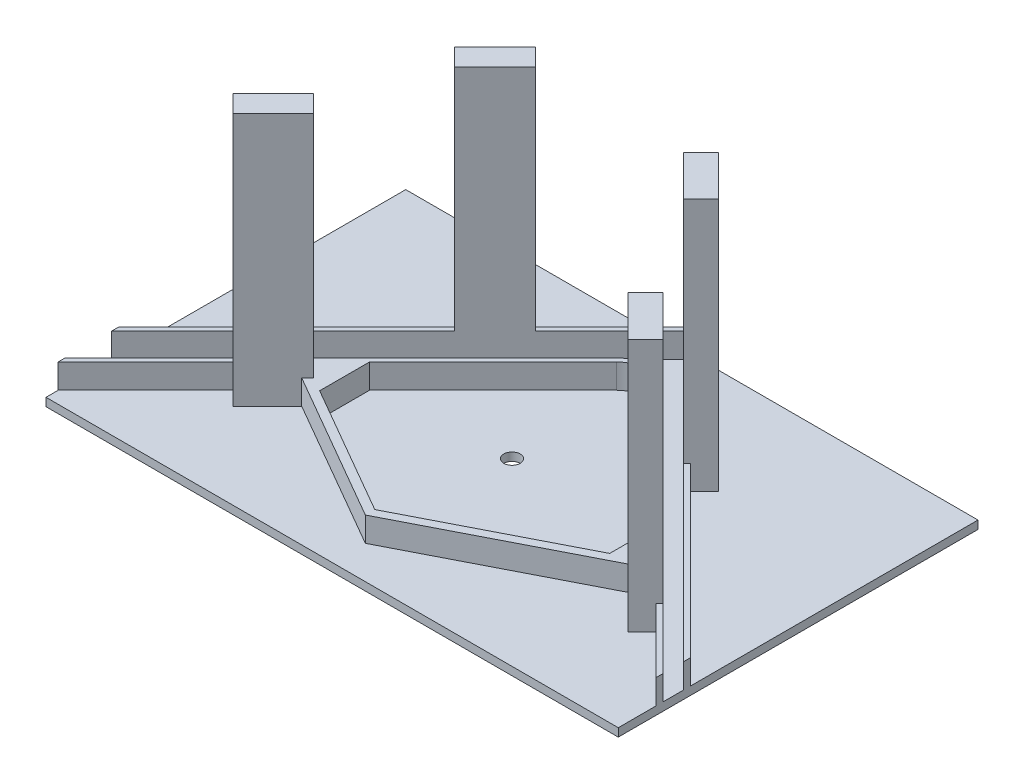
SolidWorks part; units mm, degrees
ref_plane "Alzado" through (0, 0, 0) normal (0, 0, 1) x (1, 0, 0)
ref_plane "Planta" through (0, 0, 0) normal (0, 1, 0) x (1, 0, 0)
ref_plane "Vista lateral" through (0, 0, 0) normal (1, 0, 0) x (0, 0, -1)
sketch "Croquis1" plane through (0, 0, 0) normal (0, 1, 0) x (1, 0, 0)
  line L0 (-225, -110) -> (-225, -210) construction
  line L1 (225, -110) -> (-225, -110) construction
  line L2 (225, -110) -> (225, 110) construction
  line L3 (225, 110) -> (-225, 110) construction
  line L4 (-225, -110) -> (-225, 110) construction
  line L5 (225, -110) -> (-225, 110) construction
  line L6 (225, 110) -> (-225, -110) construction
  line L7 (-225, -210) -> (225, -210) construction
  line L8 (225, -210) -> (225, -110) construction
  line L9 (-5, 0) -> (-5, -110) construction
  line L10 (5, 0) -> (5, -110) construction
  arc A0 (5, 0) -> (-5, 0) centre (0, 0) ccw construction
  point P0 (0, 0)
  dimension "D4" = 10
  dimension "D1" = 450
  dimension "D2" = 220
  dimension "D3" = 100
sketch "Croquis2" plane through (0, 0, 0) normal (0, 1, 0) x (1, 0, 0)
  line L0 (0, 133.4706) -> (0, 87.0581) construction
  line L1 (225, 110) -> (-225, -110) construction
  line L4 (-175, -110) -> (-175, 110)
  line L5 (225, -110) -> (-225, -110) construction
  line L6 (-175, 110) -> (175, 110)
  line L7 (-175, -110) -> (175, -110)
  line L8 (175, -110) -> (175, 110)
  circle A0 centre (0, 0) radius 5
  point P14 (0, -110)
  point P15 (0, 110)
  dimension "D1" = 10
  dimension "D2" = 110
  dimension "D3" = 175
extrude "Saliente-Extruir1" add sketch "Croquis2" along normal blind 20
sketch "Croquis3" plane through (0, 20, 0) normal (0, 1, 0) x (1, 0, 0)
  line L7 (-7.5056, 0) -> (-3.7528, -6.5)
  line L8 (-3.7528, -6.5) -> (3.7528, -6.5)
  line L9 (3.7528, -6.5) -> (7.5056, 0)
  line L10 (7.5056, 0) -> (3.7528, 6.5)
  line L11 (3.7528, 6.5) -> (-3.7528, 6.5)
  line L12 (-3.7528, 6.5) -> (-7.5056, 0)
  circle A0 centre (0, 0) radius 6.5 construction
  dimension "D1" = 13
extrude "Cortar-Extruir1" cut sketch "Croquis3" against normal blind 7
sketch "Croquis8" plane through (0, 20, 0) normal (0, 1, 0) x (1, 0, 0)
  line L0 (0, 132.6182) -> (0, 35.5144) construction
  line L2 (225, 110) -> (-225, 110) construction
  line L3 (21.9203, 70.3518) -> (175, -82.7279)
  line L4 (0, 105) -> (175, -70)
  line L5 (175, -110) -> (175, 110) construction
  line L8 (175, -70) -> (175, -82.7279)
  line L10 (0, 105) -> (-175, -70)
  line L11 (-175, 110) -> (-175, -110) construction
  line L12 (-175, -98.2843) -> (-6.364, 70.3518)
  line L13 (-175, -98.2843) -> (-175, -70)
  arc A0 (-6.364, 70.3518) -> (21.9203, 70.3518) centre (7.7782, 56.2096) cw
  dimension "D5" = 20
  dimension "D1" = 45
  dimension "D2" = 9
  dimension "D3" = 5
  dimension "D4" = 20
extrude "Cortar-Extruir3" cut sketch "Croquis8" against normal blind 15
sketch "Croquis9" plane through (0, 20, 0) normal (0, 1, 0) x (1, 0, 0)
  line L5 (-98.9949, -22.2792) -> (-88.3883, -32.8858)
  line L6 (-88.3883, -32.8858) -> (-113.1371, -57.6346)
  line L7 (-113.1371, -57.6346) -> (-123.7437, -47.028)
  line L8 (0, 120.8044) -> (0, 28.1611) construction
  line L9 (-98.9949, -22.2792) -> (-123.7437, -47.028)
  line L10 (-70.0137, 34.9863) -> (-80.6203, 45.5929)
  line L12 (-80.6203, 45.5929) -> (-55.8715, 70.3417)
  line L13 (-55.8715, 70.3417) -> (-45.2649, 59.7351)
  line L14 (-45.2649, 59.7351) -> (-70.0137, 34.9863)
  line L26 (0, 105) -> (-175, -70) construction
  line L27 (-175, -98.2843) -> (-6.364, 70.3518) construction
  line L28 (45.2649, 59.7351) -> (70.0137, 34.9863)
  line L29 (55.8715, 70.3417) -> (45.2649, 59.7351)
  line L30 (80.6203, 45.5929) -> (55.8715, 70.3417)
  line L31 (70.0137, 34.9863) -> (80.6203, 45.5929)
  line L32 (113.1472, -20.8751) -> (102.5406, -31.4817)
  line L33 (21.9203, 70.3518) -> (175, -82.7279) construction
  line L34 (102.5406, -31.4817) -> (127.2893, -56.2304)
  line L35 (127.2893, -56.2304) -> (137.8959, -45.6238)
  line L36 (137.8959, -45.6238) -> (113.1472, -20.8751)
  line L37 (175, -70) -> (0, 105) construction
  dimension "D1" = 15
  dimension "D2" = 35
  dimension "D3" = 35
  dimension "D4" = 15
  dimension "D5" = 15
  dimension "D6" = 70
  dimension "D7" = 35
  dimension "D8" = 160
extrude "Saliente-Extruir3" add sketch "Croquis9" along normal blind 140
sketch "Croquis10" plane through (0, 20, 0) normal (0, 1, 0) x (1, 0, 0)
  line L0 (102.5406, -31.4817) -> (127.2893, -56.2304) construction
  line L1 (-113.1371, -57.6346) -> (-88.3883, -32.8858) construction
  line L2 (80.6203, 45.5929) -> (55.8715, 70.3417) construction
  line L4 (102.5406, -31.4817) -> (127.2893, -56.2304) construction
  line L5 (-113.1371, -57.6346) -> (-88.3883, -32.8858) construction
  line L6 (80.6203, 45.5929) -> (55.8715, 70.3417) construction
  line L9 (-175, 110) -> (-175, -70) construction
  line L10 (-175, -65.7574) -> (-175, 110)
  line L11 (-175, 110) -> (0, 110)
  line L12 (175, 110) -> (175, -65.7574)
  line L13 (175, -70) -> (175, 110) construction
  line L15 (225, 110) -> (-225, 110) construction
  line L16 (0, 110) -> (175, 110)
  line L17 (-72.135, 37.1077) -> (-80.6203, 45.5929)
  line L18 (-2.1213, 107.1213) -> (-177.1213, -67.8787)
  line L19 (0, 109.2426) -> (-47.3862, 61.8564)
  line L20 (-80.6203, 45.5929) -> (-70.0137, 34.9863) construction
  line L21 (0, 105) -> (-45.2649, 59.7351) construction
  line L22 (175, -70) -> (0, 105) construction
  line L23 (0, 105) -> (-45.2649, 59.7351) construction
  line L24 (175, -70) -> (0, 105) construction
  line L25 (0, 130.436) -> (0, -133.5855) construction
  line L27 (-80.6203, 45.5929) -> (-55.8715, 70.3417)
  line L30 (-55.8715, 70.3417) -> (-47.3862, 61.8564)
  line L33 (-45.2649, 59.7351) -> (-55.8715, 70.3417) construction
  line L36 (-72.135, 37.1077) -> (-175, -65.7574)
  line L38 (175, -65.7574) -> (72.135, 37.1077)
  line L39 (177.1213, -67.8787) -> (2.1213, 107.1213) construction
  line L40 (72.135, 37.1077) -> (80.6203, 45.5929)
  line L41 (70.0137, 34.9863) -> (80.6203, 45.5929) construction
  line L42 (-88.3883, -32.8858) -> (-98.9949, -22.2792) construction
  line L43 (-96.8736, -24.4005) -> (-88.3883, -32.8858)
  line L44 (19.799, 68.2304) -> (111.0258, -22.9964)
  line L45 (-172.8787, -100.4056) -> (-4.2426, 68.2304)
  line L46 (19.799, 68.2304) -> (111.0258, -22.9964)
  line L47 (-96.8736, -24.4005) -> (-4.2426, 68.2304)
  line L49 (225, -110) -> (-225, -110) construction
  line L50 (-175, -110) -> (175, -110)
  line L51 (111.0258, -22.9964) -> (102.5406, -31.4817)
  line L53 (175, -110) -> (175, -82.7279) construction
  line L54 (175, -86.9706) -> (175, -110)
  line L55 (80.6203, 45.5929) -> (55.8715, 70.3417)
  line L56 (55.8715, 70.3417) -> (47.3862, 61.8564)
  line L57 (55.8715, 70.3417) -> (45.2649, 59.7351) construction
  line L58 (55.8715, 70.3417) -> (45.2649, 59.7351) construction
  line L59 (47.3862, 61.8564) -> (0, 109.2426)
  line L60 (-88.3883, -32.8858) -> (-113.1371, -57.6346)
  line L61 (-113.1371, -57.6346) -> (-121.6224, -49.1493)
  line L62 (-123.7437, -47.028) -> (-113.1371, -57.6346) construction
  line L63 (-121.6224, -49.1493) -> (-175, -102.5269)
  line L64 (-175, -98.2843) -> (-175, -110) construction
  line L65 (-175, -102.5269) -> (-175, -110)
  line L66 (102.5406, -31.4817) -> (127.2893, -56.2304)
  line L67 (127.2893, -56.2304) -> (135.7746, -47.7451)
  line L68 (127.2893, -56.2304) -> (137.8959, -45.6238) construction
  line L69 (135.7746, -47.7451) -> (175, -86.9706)
  arc A5 (19.799, 68.2304) -> (-4.2426, 68.2304) centre (7.7782, 56.2096) ccw
  arc A6 (19.799, 68.2304) -> (-4.2426, 68.2304) centre (7.7782, 56.2096) ccw
  dimension "D1" = 3
  dimension "D2" = 3
  dimension "D3" = 3
extrude "Cortar-Extruir4" cut sketch "Croquis10" against normal blind 15
sketch "Croquis11" plane through (0, 5, 0) normal (0, 1, 0) x (1, 0, 0)
  line L0 (0, 135.8418) -> (0, -152.8445) construction
  line L11 (-88.3883, -32.8858) -> (0, -83.9169) construction
  line L12 (95.0702, -35.3018) -> (95.0702, -7.0407)
  line L13 (0, -83.9169) -> (102.5406, -31.4817) construction
  line L15 (0, -83.9169) -> (95.0702, -35.3018)
  line L16 (-92.0486, -36.5461) -> (0, -89.6904)
  line L17 (-88.3883, -32.8858) -> (-113.1371, -57.6346) construction
  line L18 (0, -89.6904) -> (106.3606, -35.3018)
  line L19 (127.2893, -56.2304) -> (102.5406, -31.4817) construction
  line L20 (-96.8736, -24.4005) -> (-88.3883, -32.8858) construction
  line L21 (-92.0486, -36.5461) -> (-88.3883, -32.8858)
  line L22 (102.5406, -31.4817) -> (106.3606, -35.3018)
  line L23 (-79.7864, -37.8522) -> (-79.7864, -7.3133)
  line L24 (-4.2426, 68.2304) -> (-96.8736, -24.4005) construction
  line L25 (-79.7864, -7.3133) -> (-96.8736, -24.4005)
  line L26 (-96.8736, -24.4005) -> (-88.3883, -32.8858)
  line L27 (-79.7864, -37.8522) -> (0, -83.9169)
  line L28 (111.0258, -22.9964) -> (19.799, 68.2304) construction
  line L29 (95.0702, -7.0407) -> (111.0258, -22.9964)
  line L30 (111.0258, -22.9964) -> (102.5406, -31.4817)
  dimension "D1" = 5
  dimension "D2" = 165
extrude "Saliente-Extruir4" add sketch "Croquis11" along normal blind 15
